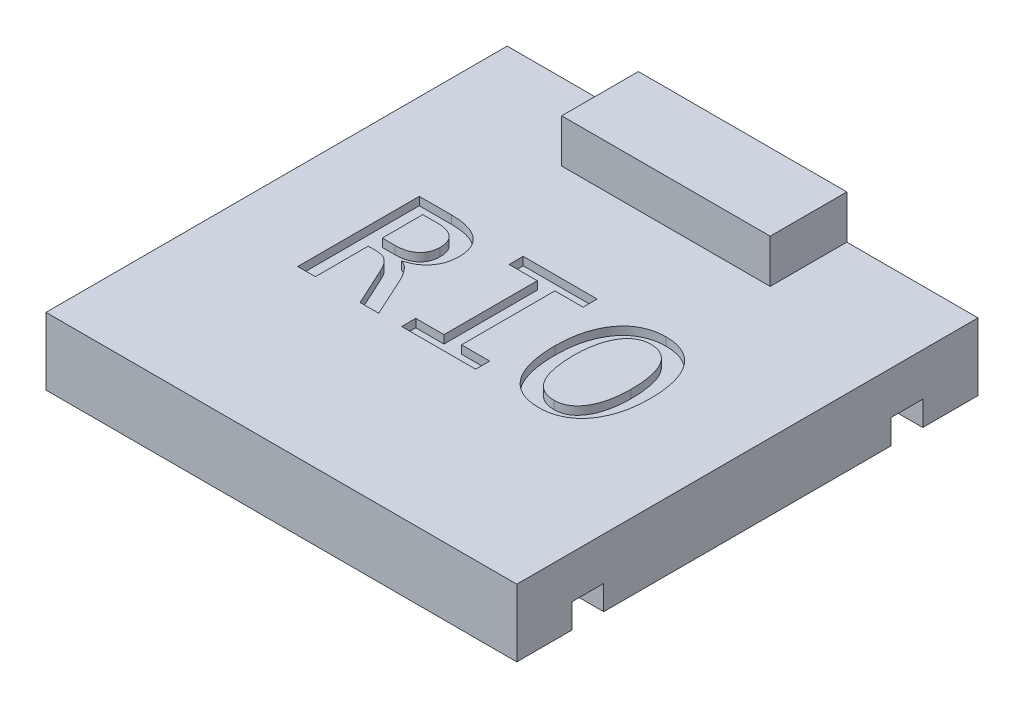
SolidWorks part; units mm, degrees
ref_plane "Front Plane" through (0, 0, 0) normal (0, 0, 1) x (1, 0, 0)
ref_plane "Top Plane" through (0, 0, 0) normal (0, 1, 0) x (1, 0, 0)
ref_plane "Right Plane" through (0, 0, 0) normal (1, 0, 0) x (0, 0, -1)
sketch "Sketch1" plane through (0, 0, 0) normal (0, 1, 0) x (1, 0, 0)
  line L1 (0, 0) -> (146.1516, 0)
  line L2 (0, 0) -> (0, 143.1798)
  line L3 (0, 143.1798) -> (146.1516, 143.1798)
  line L4 (146.1516, 0) -> (146.1516, 143.1798)
  dimension "D1" = 146.1516
  dimension "D2" = 143.1798
extrude "Boss-Extrude1" add sketch "Sketch1" along normal mid plane 34.417
sketch "Sketch3" plane through (0, 17.2085, 0) normal (0, 1, 0) x (1, 0, 0)
  line L0 (146.1516, 0) -> (146.1516, 143.1798) construction
  line L1 (0, 0) -> (146.1516, 0)
  line L2 (0, 0) -> (0, 119.38)
  line L3 (0, 119.38) -> (146.1516, 119.38)
  line L4 (146.1516, 0) -> (146.1516, 119.38)
  line L5 (146.1516, 143.1798) -> (0, 143.1798) construction
  line L6 (0, 119.38) -> (40.7162, 119.38)
  line L7 (0, 119.38) -> (0, 143.1798)
  line L8 (0, 143.1798) -> (40.7162, 143.1798)
  line L9 (40.7162, 119.38) -> (40.7162, 143.1798)
  line L11 (146.1516, 119.38) -> (105.4354, 119.38)
  line L12 (146.1516, 119.38) -> (146.1516, 143.1798)
  line L13 (146.1516, 143.1798) -> (105.4354, 143.1798)
  line L14 (105.4354, 119.38) -> (105.4354, 143.1798)
  line M1 (0, 143.1798) -> (0, 0)
  line M2 (0, 0) -> (146.1516, 0)
  line M3 (146.1516, 0) -> (146.1516, 143.1798)
  line M4 (146.1516, 143.1798) -> (0, 143.1798)
  dimension "D1" = 119.38
  dimension "D2" = 40.7162
extrude "Cut-Extrude2" cut sketch "Sketch3" against normal offset from surface (13.5128 mm away) 20.9042 contours L3 M1 M2 M3 | L3 L9 M4 M1 | L14 L3 M3 M4 up to face at (73.0758, -17.2085, -71.5899)
sketch "Sketch2" plane through (0, 3.6957, 0) normal (0, 1, 0) x (1, 0, 0)
  text T0 "RIO" font "Consolas" height in points 144
extrude "Cut-Extrude1" cut sketch "Sketch2" against normal blind 2.54
sketch "Sketch4" plane through (146.1516, 0, 0) normal (1, 0, 0) x (0, 0, -1)
  line L0 (0, -17.2085) -> (143.1798, -17.2085) construction
  line L1 (17.145, -17.2085) -> (26.9748, -17.2085)
  line L2 (17.145, -17.2085) -> (17.145, -9.5885)
  line L3 (17.145, -9.5885) -> (26.9748, -9.5885)
  line L4 (26.9748, -17.2085) -> (26.9748, -9.5885)
  line L5 (143.1798, 3.6957) -> (143.1798, -17.2085) construction
  line L6 (126.0348, -17.2085) -> (116.205, -17.2085)
  line L7 (126.0348, -17.2085) -> (126.0348, -9.5885)
  line L8 (126.0348, -9.5885) -> (116.205, -9.5885)
  line L9 (116.205, -17.2085) -> (116.205, -9.5885)
  line L10 (0, 3.6957) -> (0, -17.2085) construction
  dimension "D1" = 9.8298
  dimension "D2" = 17.145
  dimension "D3" = 17.145
  dimension "D4" = 7.62
extrude "Cut-Extrude3" cut sketch "Sketch4" against normal blind 10.16
ref_plane "Plane1" through (73.0758, 0, 0) normal (-1, 0, 0) x (0, 0, 1)
mirror "Mirror1" about plane through (73.0758, 0, 0) normal (-1, 0, 0) of "Cut-Extrude3"
